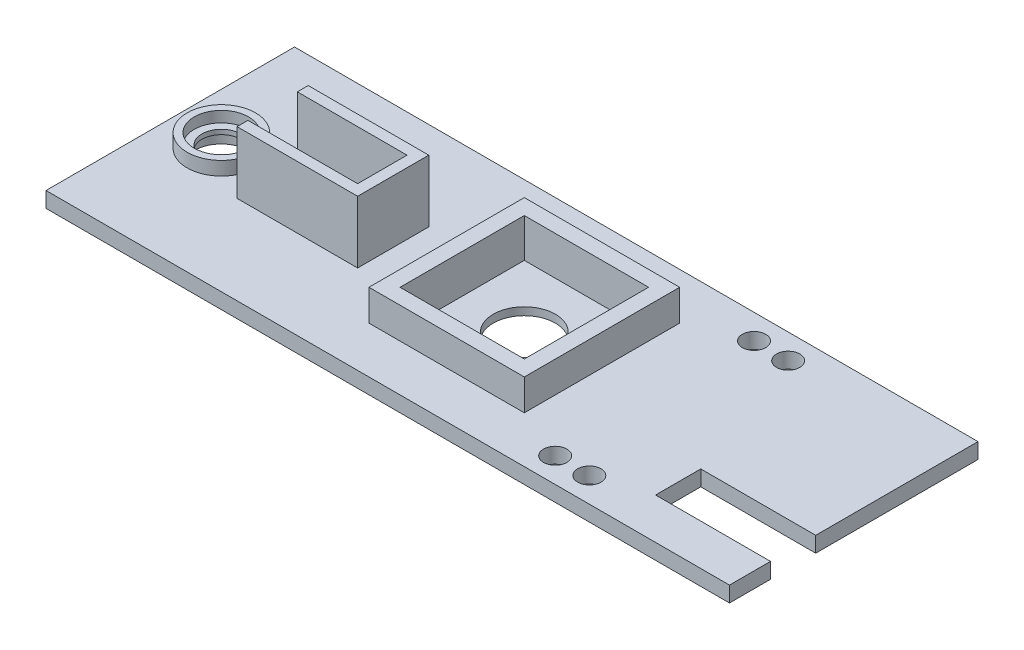
SolidWorks part; units mm, degrees
ref_plane "Front Plane" through (0, 0, 0) normal (0, 0, 1) x (1, 0, 0)
ref_plane "Top Plane" through (0, 0, 0) normal (0, 1, 0) x (1, 0, 0)
ref_plane "Right Plane" through (0, 0, 0) normal (1, 0, 0) x (0, 0, -1)
sketch "Sketch1" plane through (0, 0, 0) normal (0, 1, 0) x (1, 0, 0)
  line L1 (-279.4, -50.8) -> (0, -50.8)
  line L2 (-279.4, -50.8) -> (-279.4, 50.8)
  line L3 (-279.4, 50.8) -> (0, 50.8)
  line L4 (0, -50.8) -> (0, 50.8)
  point P0 (0, 0)
  dimension "D2" = 101.6
extrude "Boss-Extrude1" add sketch "Sketch1" along normal blind 6.35
sketch "Sketch2" plane through (0, 6.35, 0) normal (0, 1, 0) x (1, 0, 0)
  circle A0 centre (-258.5106, 0) radius 13.97
extrude "Boss-Extrude3" add sketch "Sketch2" along normal blind 5.5562
sketch "Sketch9" plane through (0, 11.9062, 0) normal (0, 1, 0) x (1, 0, 0)
  circle A0 centre (-258.5106, 0) radius 11.1125
extrude "Cut-Extrude4" cut sketch "Sketch9" against normal blind 4.445
sketch "Sketch10" plane through (0, 0, 0) normal (0, -1, 0) x (-1, 0, 0)
  circle A0 centre (258.5106, 0) radius 11.1125
extrude "Cut-Extrude5" cut sketch "Sketch10" against normal blind 5.5562
sketch "Sketch11" plane through (0, 7.4613, 0) normal (0, 1, 0) x (1, 0, 0)
  circle A0 centre (-258.5106, 0) radius 7.9375
extrude "Cut-Extrude6" cut sketch "Sketch11" against normal through all
sketch "Sketch12" plane through (0, 6.35, 0) normal (0, 1, 0) x (1, 0, 0)
  circle A0 centre (-134.6662, 0) radius 12.7
  dimension "D1" = 25.4
extrude "Cut-Extrude7" cut sketch "Sketch12" against normal through all
sketch "Sketch22" plane through (0, 6.35, 0) normal (0, 1, 0) x (1, 0, 0)
  line L1 (-102.9162, -31.75) -> (-166.4162, -31.75)
  line L2 (-102.9162, -31.75) -> (-102.9162, 31.75)
  line L3 (-102.9162, 31.75) -> (-166.4162, 31.75)
  line L4 (-166.4162, -31.75) -> (-166.4162, 31.75)
  line L5 (-102.9162, -31.75) -> (-166.4162, 31.75) construction
  line L6 (-102.9162, 31.75) -> (-166.4162, -31.75) construction
  circle A0 centre (-134.6662, 0) radius 12.7 construction
  point P0 (-134.6662, 0)
extrude "Boss-Extrude7" add sketch "Sketch22" along normal blind 12.7
sketch "Sketch25" plane through (0, 19.05, 0) normal (0, 1, 0) x (1, 0, 0)
  line L1 (-109.2662, -25.4) -> (-160.0662, -25.4)
  line L2 (-109.2662, -25.4) -> (-109.2662, 25.4)
  line L3 (-109.2662, 25.4) -> (-160.0662, 25.4)
  line L4 (-160.0662, -25.4) -> (-160.0662, 25.4)
  line L5 (-109.2662, -25.4) -> (-160.0662, 25.4) construction
  line L6 (-109.2662, 25.4) -> (-160.0662, -25.4) construction
  circle A0 centre (-134.6662, 0) radius 12.7 construction
  point P0 (-134.6662, 0)
  dimension "D1" = 50.8
  dimension "D2" = 50.8
extrude "Cut-Extrude11" cut sketch "Sketch25" against normal blind 15.875
sketch "Sketch32" plane through (0, 6.35, 0) normal (0, 1, 0) x (1, 0, 0)
  line L3 (-279.4, -50.8) -> (0, -50.8) construction
  line L5 (0, 50.8) -> (-279.4, 50.8) construction
  circle A0 centre (-67.442, -40.64) radius 4.7625
  circle A1 centre (-81.412, -40.64) radius 4.7625
  circle A2 centre (-67.442, 40.64) radius 4.7625
  circle A3 centre (-81.412, 40.64) radius 4.7625
  dimension "D1" = 10.16
  dimension "D2" = 10.16
  dimension "D3" = 10.16
  dimension "D4" = 10.16
  dimension "D5" = 13.97
  dimension "D6" = 13.97
  dimension "D7" = 81.28
extrude "Cut-Extrude12" cut sketch "Sketch32" against normal blind 6.35
sketch "Sketch38" plane through (0, 6.35, 0) normal (0, 1, 0) x (1, 0, 0)
  line L0 (0, -50.8) -> (0, 50.8) construction
  line L1 (0, -34.0128) -> (-46.99, -34.0128)
  line L2 (0, -34.0128) -> (0, -15.5426)
  line L3 (0, -15.5426) -> (-46.99, -15.5426)
  line L4 (-46.99, -34.0128) -> (-46.99, -15.5426)
  line L6 (-279.4, -50.8) -> (0, -50.8) construction
  dimension "D1" = 35.2574
  dimension "D2" = 18.4703
  dimension "D3" = 46.99
extrude "Cut-Extrude13" cut sketch "Sketch38" against normal blind 6.35
sketch "Sketch49" plane through (0, 6.35, 0) normal (0, 1, 0) x (1, 0, 0)
  line L0 (-279.4, 50.8) -> (-279.4, -50.8) construction
  line L1 (-192.7106, -10.1) -> (-233.1106, -10.1)
  line L2 (-192.7106, -10.1) -> (-192.7106, 10.1)
  line L3 (-192.7106, 10.1) -> (-233.1106, 10.1)
  line L4 (-233.1106, -10.1) -> (-233.1106, 10.1)
  line L5 (-192.7106, -10.1) -> (-233.1106, 10.1) construction
  line L6 (-192.7106, 10.1) -> (-233.1106, -10.1) construction
  circle A2 centre (-258.5106, 0) radius 13.97 construction
  point P0 (-212.9106, 0)
  point P13 (-279.4, 0)
  dimension "D1" = 40.4
  dimension "D2" = 25.4
sketch "Sketch50" plane through (0, 6.35, 0) normal (0, 1, 0) x (1, 0, 0)
  line L0 (-233.1106, -10.1) -> (-233.1106, 10.1) construction
  line L1 (-237.5556, -14.545) -> (-188.2656, -14.545)
  line L2 (-237.5556, -14.545) -> (-237.5556, 14.545)
  line L3 (-237.5556, 14.545) -> (-188.2656, 14.545)
  line L4 (-188.2656, -14.545) -> (-188.2656, 14.545)
  line L5 (-237.5556, -14.545) -> (-188.2656, 14.545) construction
  line L6 (-237.5556, 14.545) -> (-188.2656, -14.545) construction
  line L7 (-192.7106, 10.1) -> (-233.1106, 10.1) construction
  point P0 (-212.9106, 0)
  dimension "D1" = 4.445
  dimension "D2" = 4.445
extrude "Boss-Extrude14" add sketch "Sketch50" along normal blind 25.4
extrude "Cut-Extrude19" cut sketch "Sketch49" along normal through all
sketch "Sketch52" plane through (-233.1106, 0, 0) normal (1, 0, 0) x (0, 0, -1)
  line L1 (10.1, 31.75) -> (-10.1, 31.75)
  line L2 (10.1, 31.75) -> (10.1, 6.35)
  line L3 (10.1, 6.35) -> (-10.1, 6.35)
  line L4 (-10.1, 31.75) -> (-10.1, 6.35)
extrude "Cut-Extrude20" cut sketch "Sketch52" against normal up to surface (4.445 mm away) up to face at (-237.5556, 19.05, 0)
sketch "Sketch53" plane through (0, 6.35, 0) normal (0, 1, 0) x (1, 0, 0)
  line L1 (-237.5556, 10.1) -> (-192.7106, 10.1)
  line L2 (-237.5556, 10.1) -> (-237.5556, -10.1)
  line L3 (-237.5556, -10.1) -> (-192.7106, -10.1)
  line L4 (-192.7106, 10.1) -> (-192.7106, -10.1)
extrude "Boss-Extrude15" add sketch "Sketch53" along normal blind 4.7606
sketch "Sketch55" plane through (0, 11.1106, 0) normal (0, 1, 0) x (1, 0, 0)
  line L7 (-237.5556, 10.1) -> (-192.7106, 10.1)
  line L8 (-237.5556, 10.1) -> (-237.5556, -10.1)
  line L9 (-237.5556, -10.1) -> (-192.7106, -10.1)
  line L10 (-192.7106, 10.1) -> (-192.7106, -10.1)
extrude "Cut-Extrude21" cut sketch "Sketch55" against normal through all
sketch "Sketch56" plane through (0, 6.35, 0) normal (0, 1, 0) x (1, 0, 0)
  line L0 (-237.5556, -10.1) -> (-237.5556, 10.1) construction
  line L1 (-207.0756, 10.1) -> (-221.0456, 10.1)
  line L2 (-207.0756, 10.1) -> (-207.0756, -10.1)
  line L3 (-207.0756, -10.1) -> (-221.0456, -10.1)
  line L4 (-221.0456, 10.1) -> (-221.0456, -10.1)
  line L5 (-192.7106, 10.1) -> (-237.5556, 10.1) construction
  point P8 (-237.5556, 0)
  dimension "D1" = 30.48
  dimension "D2" = 16.51
  dimension "D3" = 20.2
  dimension "D4" = 20.2
extrude "Boss-Extrude16" add sketch "Sketch56" against normal up to surface (6.35 mm away) contours L2 L1 L4 L3 up to face at (-215.1331, 0, 0)
